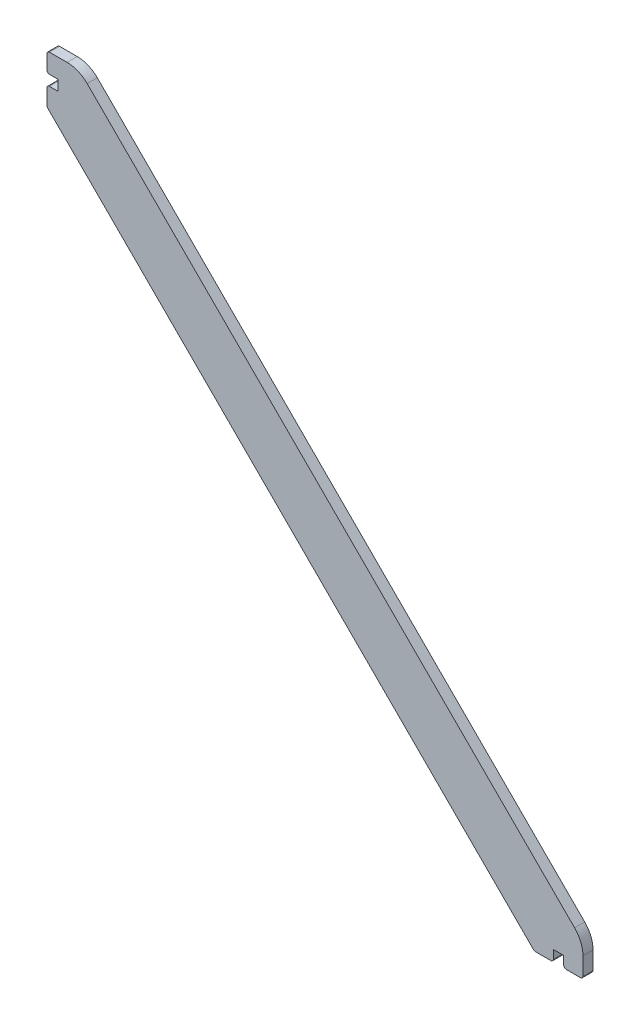
SolidWorks part; units mm, degrees
ref_plane "Front Plane" through (0, 0, 0) normal (0, 0, 1) x (1, 0, 0)
ref_plane "Top Plane" through (0, 0, 0) normal (0, 1, 0) x (1, 0, 0)
ref_plane "Right Plane" through (0, 0, 0) normal (1, 0, 0) x (0, 0, -1)
sketch "Sketch1" plane through (0, 0, 0) normal (0, 0, 1) x (1, 0, 0)
  line L0 (-104.305, 88.395) -> (92.045, -107.955) construction
  line L1 (-100, -100) -> (100, -100) construction
  line L2 (-100, -100) -> (-100, 100) construction
  line L3 (-100, 100) -> (100, 100) construction
  line L4 (100, -100) -> (100, 100) construction
  line L5 (-100, -100) -> (100, 100) construction
  line L6 (-100, 100) -> (100, -100) construction
  line L7 (-92.045, 107.955) -> (107.955, -92.045) construction
  line L8 (-100, 107.6) -> (100, 107.6) construction
  line L9 (-100, 100) -> (-130.5198, 100) construction
  line L10 (-100, 95.9) -> (-130.5198, 95.9) construction
  line L11 (-96.35, 107.6) -> (-103.305, 107.6)
  line L12 (-104.305, 106.6) -> (-104.305, 101)
  line L13 (-103.305, 100) -> (-100, 100)
  line L14 (-100, 100) -> (-100, 95.9)
  line L15 (-100, 95.9) -> (-103.305, 95.9)
  line L16 (-96.35, 96.35) -> (-96.35, 132.7328) construction
  line L17 (-104.305, 88.395) -> (-104.305, 132.7328) construction
  line L18 (-107.955, 92.045) -> (92.045, -107.955) construction
  line L19 (-104.305, 94.9) -> (-104.305, 88.8093)
  line L20 (-104.0121, 88.1022) -> (-100, 84.0901)
  line L21 (-88.395, 104.305) -> (-84.0901, 100)
  line L22 (104.305, -88.395) -> (100, -84.0901)
  line L23 (88.1022, -104.0121) -> (84.0901, -100)
  line L24 (94.9, -104.305) -> (88.8093, -104.305)
  line L25 (95.9, -100) -> (95.9, -103.305)
  line L26 (100, -100) -> (95.9, -100)
  line L27 (100, -103.305) -> (100, -100)
  line L28 (106.6, -104.305) -> (101, -104.305)
  line L29 (107.6, -96.35) -> (107.6, -103.305)
  line L30 (-84.0901, 100) -> (100, -84.0901)
  line L31 (-100, 84.0901) -> (84.0901, -100)
  circle A0 centre (-96.35, 96.35) radius 11.25 construction
  arc A1 (-88.395, 104.305) -> (-96.35, 107.6) centre (-96.35, 96.35) ccw
  arc A2 (-103.305, 107.6) -> (-104.305, 106.6) centre (-103.305, 106.6) ccw
  arc A3 (-103.305, 95.9) -> (-104.305, 94.9) centre (-103.305, 94.9) ccw
  arc A4 (-104.305, 101) -> (-103.305, 100) centre (-103.305, 101) ccw
  arc A5 (-104.305, 88.8093) -> (-104.0121, 88.1022) centre (-103.305, 88.8093) ccw
  circle A6 centre (96.35, -96.35) radius 11.25 construction
  arc A7 (88.8093, -104.305) -> (88.1022, -104.0121) centre (88.8093, -103.305) cw
  arc A8 (101, -104.305) -> (100, -103.305) centre (101, -103.305) cw
  arc A9 (95.9, -103.305) -> (94.9, -104.305) centre (94.9, -103.305) cw
  arc A10 (107.6, -103.305) -> (106.6, -104.305) centre (106.6, -103.305) cw
  arc A11 (104.305, -88.395) -> (107.6, -96.35) centre (96.35, -96.35) cw
  point P0 (0, 0)
  point P30 (-104.305, 95.9)
  point P33 (-104.305, 100)
  point P57 (100, -104.305)
  point P58 (95.9, -104.305)
  dimension "D7" = 1
  dimension "D8" = 1
  dimension "SIZE" = 200
  dimension "D2" = 11.25
  dimension "D6" = 4.305
  dimension "D3" = 11.25
  dimension "D4" = 7.6
  dimension "D5" = 4.1
extrude "Boss-Extrude1" add sketch "Sketch1" along normal blind 4
